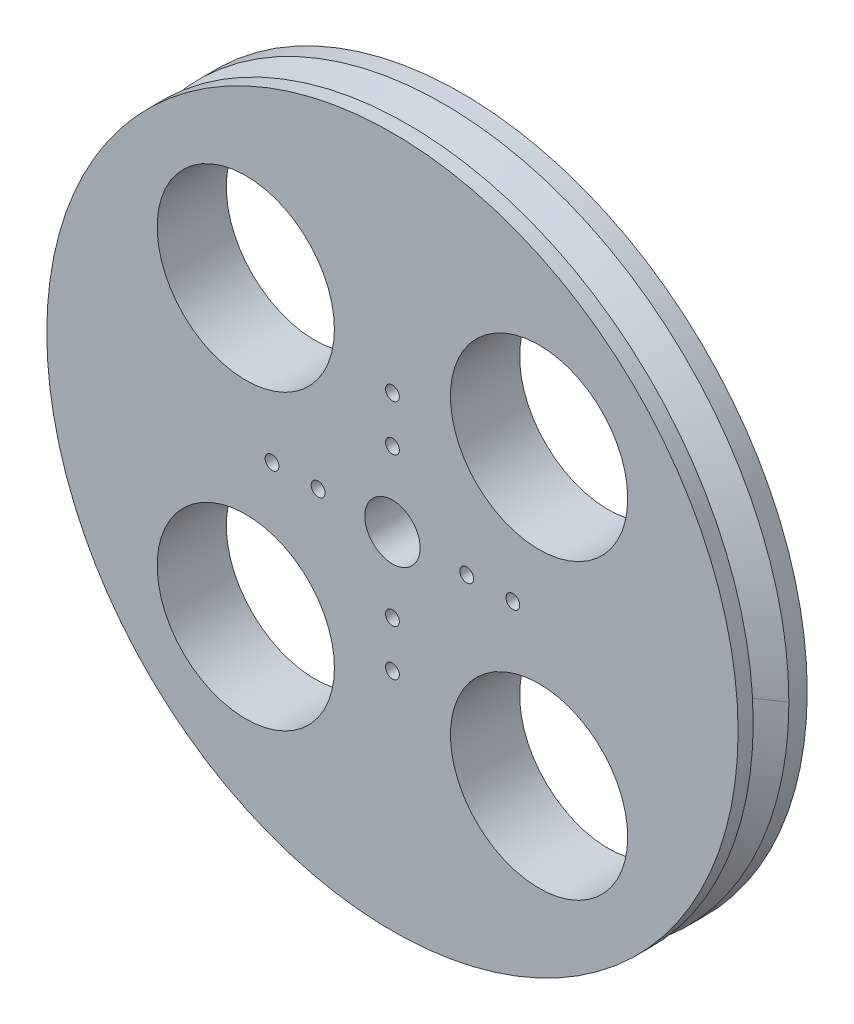
SolidWorks part; units mm, degrees
material "ABS PC"
ref_plane "Plan de face" through (0, 0, 0) normal (0, 0, 1) x (1, 0, 0)
ref_plane "Plan de dessus" through (0, 0, 0) normal (0, 1, 0) x (1, 0, 0)
ref_plane "Plan de droite" through (0, 0, 0) normal (1, 0, 0) x (0, 0, -1)
sketch "Esquisse2" plane through (0, 0, 0) normal (0, 0, 1) x (1, 0, 0)
  line L0 (0, 30) -> (0, -30) construction
  line L1 (-30, 0) -> (30, 0) construction
  line L2 (-1.997, 14.1591) -> (-2.5308, 4.3902)
  line L3 (2.5308, 4.3902) -> (1.997, 14.1591)
  line L4 (14.1591, 1.997) -> (4.3902, 2.5308)
  line L5 (4.3902, -2.5308) -> (14.1591, -1.997)
  line L6 (1.997, -14.1591) -> (2.5308, -4.3902)
  line L7 (-2.5308, -4.3902) -> (-1.997, -14.1591)
  line L8 (-14.1591, -1.997) -> (-2.2091, -2.65)
  line L9 (2.2091, -2.65) -> (14.1591, -1.997)
  line L10 (14.1591, 1.997) -> (2.2091, 2.65)
  line L11 (-2.2091, 2.65) -> (-14.1591, 1.997)
  line L12 (-14.1591, -1.997) -> (-4.3902, -2.5308)
  line L13 (-21.2132, 21.2132) -> (21.2132, -21.2132) construction
  line L15 (-4.3902, 2.5308) -> (-14.1591, 1.997)
  arc A0 (1.997, 14.1591) -> (-1.997, 14.1591) centre (0, 14.05) ccw
  circle A1 centre (0, 10.45) radius 0.6
  circle A2 centre (0, 6.45) radius 0.6
  arc A3 (14.1591, -1.997) -> (14.1591, 1.997) centre (14.05, 0) ccw
  circle A4 centre (0, 0) radius 30
  circle A5 centre (0, 0) radius 2.4
  circle A6 centre (10.45, 0) radius 0.6
  arc A7 (2.5308, 4.3902) -> (4.3902, 2.5308) centre (0, 0) cw
  arc A8 (-2.2091, -2.65) -> (2.2091, -2.65) centre (0, 0) ccw
  arc A9 (14.1591, -1.997) -> (14.1591, 1.997) centre (14.05, 0) ccw
  arc A10 (2.2091, 2.65) -> (-2.2091, 2.65) centre (0, 0) ccw
  arc A11 (-14.1591, 1.997) -> (-14.1591, -1.997) centre (-14.05, 0) ccw
  circle A12 centre (6.45, 0) radius 0.6
  arc A13 (-1.997, -14.1591) -> (1.997, -14.1591) centre (0, -14.05) ccw
  circle A14 centre (0, -10.45) radius 0.6
  arc A15 (-14.1591, 1.997) -> (-14.1591, -1.997) centre (-14.05, 0) ccw
  arc A16 (2.5308, -4.3902) -> (4.3902, -2.5308) centre (0, 0) ccw
  circle A17 centre (-10.45, 0) radius 0.6 construction
  circle A18 centre (-6.45, 0) radius 0.6 construction
  circle A19 centre (0, -6.45) radius 0.6
  arc A20 (-2.5308, 4.3902) -> (-4.3902, 2.5308) centre (0, 0) ccw
  circle A21 centre (-10.45, 0) radius 0.6
  circle A22 centre (-6.45, 0) radius 0.6
  arc A23 (-4.3902, -2.5308) -> (-2.5308, -4.3902) centre (0, 0) ccw
  circle A24 centre (-12.7279, 12.7279) radius 7.6923
  circle A25 centre (12.7279, 12.7279) radius 7.6923
  circle A26 centre (12.7279, -12.7279) radius 7.6923
  circle A27 centre (-12.7279, -12.7279) radius 7.6923
  point P53 (0, 0)
  point P56 (0, 0)
  point P68 (0, 0)
  dimension "D3" = 135
  dimension "D4" = 18
  dimension "D5" = 60
  dimension "D6" = 4.8
  dimension "D1" = 0
  dimension "D2" = 4
  dimension "D7" = 4
extrude "Boss.-Extru.1" add sketch "Esquisse2" along normal blind 6 contours A5 | A4 | A21 | A22 | A1 | A2 | A6 | A12 | A24 | A19 | A14 | A25 | A27 | A26
sketch "Esquisse3" plane through (0, 0, 0) normal (0, 0, -1) x (-1, 0, 0)
  line L8 (-2.5308, -4.3902) -> (-1.997, -14.1591)
  line L9 (1.997, -14.1591) -> (2.5308, -4.3902)
  line L10 (4.3902, -2.5308) -> (14.1591, -1.997)
  line L11 (14.1591, 1.997) -> (4.3902, 2.5308)
  line L12 (2.5308, 4.3902) -> (1.997, 14.1591)
  line L13 (-1.997, 14.1591) -> (-2.5308, 4.3902)
  line L14 (-4.3902, 2.5308) -> (-14.1591, 1.997)
  line L15 (-14.1591, -1.997) -> (-4.3902, -2.5308)
  line L16 (-2.5308, -4.3902) -> (-1.997, -14.1591)
  line L17 (1.997, -14.1591) -> (2.5308, -4.3902)
  line L18 (4.3902, -2.5308) -> (14.1591, -1.997)
  line L19 (14.1591, 1.997) -> (4.3902, 2.5308)
  line L20 (2.5308, 4.3902) -> (1.997, 14.1591)
  line L21 (-1.997, 14.1591) -> (-2.5308, 4.3902)
  line L22 (-4.3902, 2.5308) -> (-14.1591, 1.997)
  line L23 (-14.1591, -1.997) -> (-4.3902, -2.5308)
  arc A32 (-1.997, -14.1591) -> (1.997, -14.1591) centre (0, -14.05) ccw
  arc A33 (2.5308, -4.3902) -> (4.3902, -2.5308) centre (0, 0) ccw
  arc A34 (14.1591, -1.997) -> (14.1591, 1.997) centre (14.05, 0) ccw
  arc A35 (4.3902, 2.5308) -> (2.5308, 4.3902) centre (0, 0) ccw
  arc A36 (1.997, 14.1591) -> (-1.997, 14.1591) centre (0, 14.05) ccw
  arc A37 (-2.5308, 4.3902) -> (-4.3902, 2.5308) centre (0, 0) ccw
  arc A38 (-14.1591, 1.997) -> (-14.1591, -1.997) centre (-14.05, 0) ccw
  arc A39 (-4.3902, -2.5308) -> (-2.5308, -4.3902) centre (0, 0) ccw
  arc A40 (-1.997, -14.1591) -> (1.997, -14.1591) centre (0, -14.05) ccw
  arc A41 (2.5308, -4.3902) -> (4.3902, -2.5308) centre (0, 0) ccw
  arc A42 (14.1591, -1.997) -> (14.1591, 1.997) centre (14.05, 0) ccw
  arc A43 (4.3902, 2.5308) -> (2.5308, 4.3902) centre (0, 0) ccw
  arc A44 (1.997, 14.1591) -> (-1.997, 14.1591) centre (0, 14.05) ccw
  arc A45 (-2.5308, 4.3902) -> (-4.3902, 2.5308) centre (0, 0) ccw
  arc A46 (-14.1591, 1.997) -> (-14.1591, -1.997) centre (-14.05, 0) ccw
  arc A47 (-4.3902, -2.5308) -> (-2.5308, -4.3902) centre (0, 0) ccw
  dimension "D13" = 0
extrude "Enlèv. mat.-Extru.1" cut sketch "Esquisse3" against normal blind 2
sketch "Esquisse4" plane through (0, 0, 0) normal (0, 1, 0) x (1, 0, 0)
  line L0 (-31.3897, -5.4733) -> (-27.5216, -3.2903)
  line L1 (-27.5216, -3.2903) -> (-31.3897, -0.6382)
  line L2 (-31.3897, -0.6382) -> (-31.3897, -5.4733)
sweep "Enlèvement de matière-Balayage1" cut profiles "Esquisse4" path edge at (30, 0, 0)
